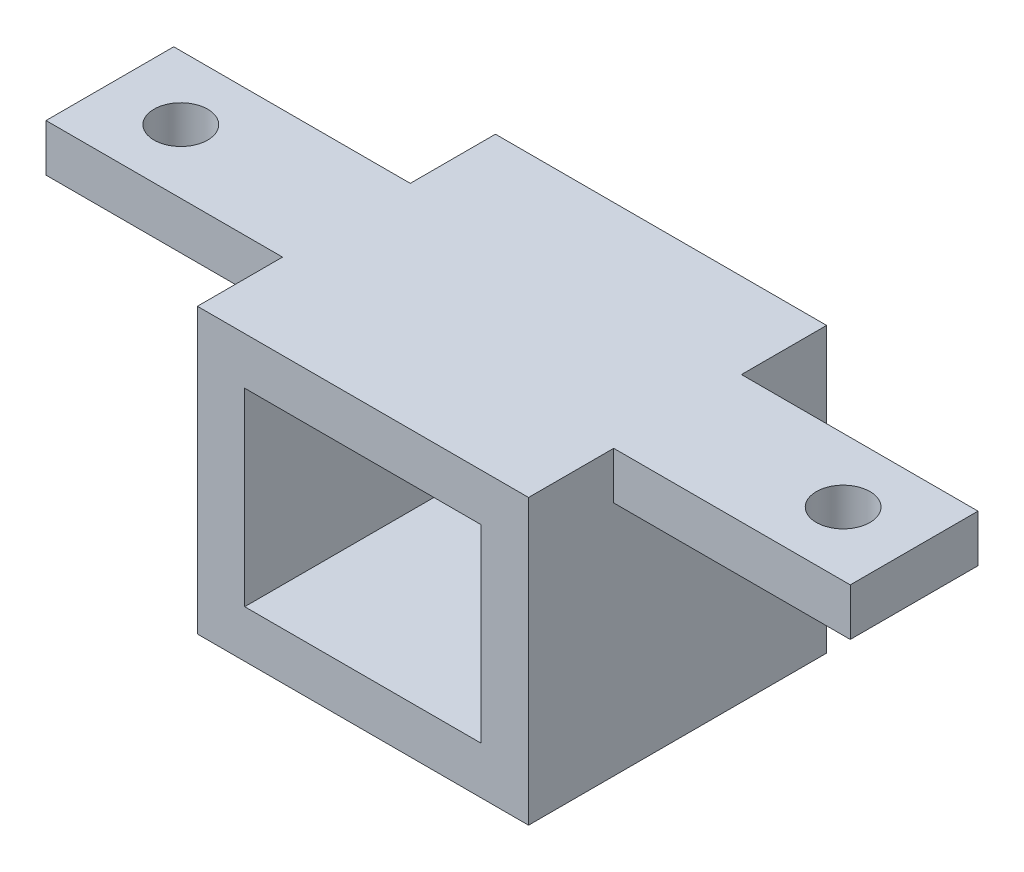
SolidWorks part; units mm, degrees
ref_plane "Front Plane" through (0, 0, 0) normal (0, 0, 1) x (1, 0, 0)
ref_plane "Top Plane" through (0, 0, 0) normal (0, 1, 0) x (1, 0, 0)
ref_plane "Right Plane" through (0, 0, 0) normal (1, 0, 0) x (0, 0, -1)
sketch "Sketch1" plane through (0, 0, 0) normal (0, 1, 0) x (1, 0, 0)
  line L1 (8.89, -8.001) -> (-8.89, -8.001)
  line L2 (8.89, -8.001) -> (8.89, 8.001)
  line L3 (8.89, 8.001) -> (-8.89, 8.001)
  line L4 (-8.89, -8.001) -> (-8.89, 8.001)
  line L5 (0, 8.001) -> (0, -8.001) construction
  line L6 (8.89, 0) -> (-8.89, 0) construction
  line L7 (-8.89, 3.429) -> (-21.59, 3.429)
  line L8 (-8.89, 3.429) -> (-8.89, -3.429)
  line L9 (-8.89, -3.429) -> (-21.59, -3.429)
  line L10 (-21.59, 3.429) -> (-21.59, -3.429)
  line L11 (8.89, 3.429) -> (21.59, 3.429)
  line L12 (8.89, 3.429) -> (8.89, -3.429)
  line L13 (8.89, -3.429) -> (21.59, -3.429)
  line L14 (21.59, 3.429) -> (21.59, -3.429)
  point P0 (0, 0)
  dimension "D1" = 12.7
  dimension "D2" = 12.7
  dimension "D3" = 17.78
  dimension "D4" = 4.572
  dimension "D5" = 16.002
  dimension "D6" = 4.572
  dimension "D7" = 4.572
  dimension "D8" = 4.572
extrude "Boss-Extrude1" add sketch "Sketch1" along normal blind 2.54 contours L4 L1 L2 L3 | L7 L10 L9 L4 | L14 L11 L2 L13
sketch "Sketch2" plane through (0, 0, 0) normal (0, -1, 0) x (1, 0, 0)
  line L0 (21.59, -3.429) -> (21.59, 3.429) construction
  line L1 (-21.59, -3.429) -> (-21.59, 3.429) construction
  circle A0 centre (-17.78, 0) radius 1.44
  circle A1 centre (17.78, 0) radius 1.44
  dimension "D1" = 3.81
  dimension "D2" = 3.81
extrude "Cut-Extrude1" cut sketch "Sketch2" against normal through all contours A1 | A0
sketch "Sketch3" plane through (0, 0, 0) normal (0, -1, 0) x (-1, 0, 0)
  line L0 (-8.89, 8.001) -> (8.89, 8.001) construction
  line L1 (8.89, -8.001) -> (6.35, -8.001)
  line L2 (8.89, -8.001) -> (8.89, 8.001)
  line L3 (8.89, 8.001) -> (6.35, 8.001)
  line L4 (6.35, -8.001) -> (6.35, 8.001)
  line L6 (-8.89, -8.001) -> (-6.35, -8.001)
  line L7 (-8.89, -8.001) -> (-8.89, 8.001)
  line L8 (-8.89, 8.001) -> (-6.35, 8.001)
  line L9 (-6.35, -8.001) -> (-6.35, 8.001)
  line L10 (6.35, 8.001) -> (-6.35, 8.001)
  line L11 (6.35, 8.001) -> (6.35, 5.461)
  line L12 (6.35, 5.461) -> (-6.35, 5.461)
  line L13 (-6.35, 8.001) -> (-6.35, 5.461)
  line M9 (8.89, -8.001) -> (8.89, -3.429)
  line M13 (8.89, 3.429) -> (8.89, 8.001)
  line M14 (8.89, 8.001) -> (-8.89, 8.001)
  line M15 (-8.89, 8.001) -> (-8.89, 3.429)
  line M19 (-8.89, -3.429) -> (-8.89, -8.001)
  line M20 (-8.89, -8.001) -> (8.89, -8.001)
  dimension "D1" = 2.54
  dimension "D2" = 2.54
  dimension "D3" = 2.54
extrude "Boss-Extrude2" add sketch "Sketch3" along normal blind 10.16 contours L4 L2 M20 M9 M13 M14 | L12 L4 L9 M14 | L9 L7 M20 M14 M15 M19
sketch "Sketch4" plane through (0, -10.16, 0) normal (0, -1, 0) x (-1, 0, 0)
  line L1 (8.89, -8.001) -> (-8.89, -8.001)
  line L2 (8.89, -8.001) -> (8.89, 8.001)
  line L3 (8.89, 8.001) -> (-8.89, 8.001)
  line L4 (-8.89, -8.001) -> (-8.89, 8.001)
extrude "Boss-Extrude3" add sketch "Sketch4" along normal blind 2.54
sketch "Sketch5" plane through (0, 0, -8.001) normal (0, 0, -1) x (-1, 0, 0)
  line L0 (8.89, -12.7) -> (-8.89, -12.7) construction
  circle A0 centre (0, -5.08) radius 2
  circle A1 centre (4.699, -5.08) radius 0.8
  circle A2 centre (-4.699, -5.08) radius 0.8
  dimension "D1" = 7.62
  dimension "D2" = 7.62
  dimension "D3" = 7.62
  dimension "D4" = 4.699
  dimension "D5" = 4.699
extrude "Cut-Extrude2" cut sketch "Sketch5" against normal through all contours A2 | A0 | A1
